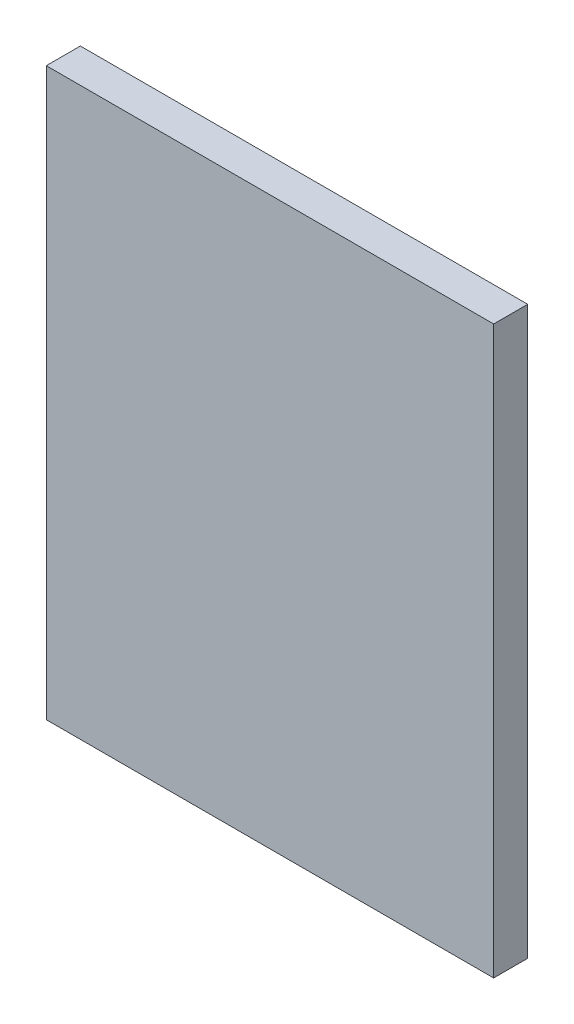
SolidWorks part; units mm, degrees
ref_plane "Plan de face" through (0, 0, 0) normal (0, 0, 1) x (1, 0, 0)
ref_plane "Plan de dessus" through (0, 0, 0) normal (0, 1, 0) x (1, 0, 0)
ref_plane "Plan de droite" through (0, 0, 0) normal (1, 0, 0) x (0, 0, -1)
sketch "Esquisse1" plane through (0, 0, 0) normal (0, 0, 1) x (1, 0, 0)
  line L0 (-6.4262, 7.38) -> (6.7056, 7.38)
  line L1 (6.7056, 7.38) -> (6.7056, -9.2456)
  line L2 (6.7056, -9.2456) -> (-6.4262, -9.2456)
  line L3 (-6.4262, -9.2456) -> (-6.4262, 7.38)
extrude "Component_Outline" add sketch "Esquisse1" along normal blind 1 separate body
sketch3d "Esquisse3D1"
  line L0 (0, 0, 0) -> (1, 0, 0)
  line L1 (0, 0, 0) -> (0, 1, 0)
  line L2 (0, 0, 0) -> (0, 0, 1)
  point P0 (0, 0, 0)
